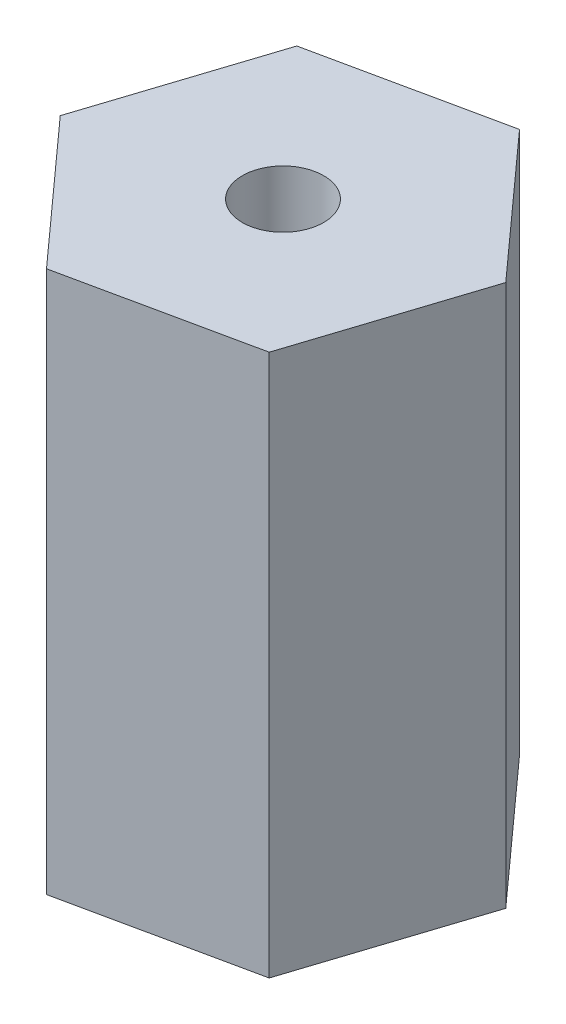
SolidWorks part; units mm, degrees
ref_plane "Front Plane" through (0, 0, 0) normal (0, 0, 1) x (1, 0, 0)
ref_plane "Top Plane" through (0, 0, 0) normal (0, 1, 0) x (1, 0, 0)
ref_plane "Right Plane" through (0, 0, 0) normal (1, 0, 0) x (0, 0, -1)
sketch "Sketch2" plane through (0, 0, 0) normal (0, 1, 0) x (1, 0, 0)
  line L1 (4.6385, -5.1463) -> (6.7761, 1.444)
  line L2 (6.7761, 1.444) -> (2.1375, 6.5902)
  line L3 (2.1375, 6.5902) -> (-4.6385, 5.1463)
  line L4 (-4.6385, 5.1463) -> (-6.7761, -1.444)
  line L5 (-6.7761, -1.444) -> (-2.1375, -6.5902)
  line L6 (-2.1375, -6.5902) -> (4.6385, -5.1463)
  circle A0 centre (0, 0) radius 6 construction
  circle A1 centre (0, 0) radius 1.5
  dimension "D1" = 12
  dimension "D2" = 3
extrude "Boss-Extrude1" add sketch "Sketch2" along normal blind 20
